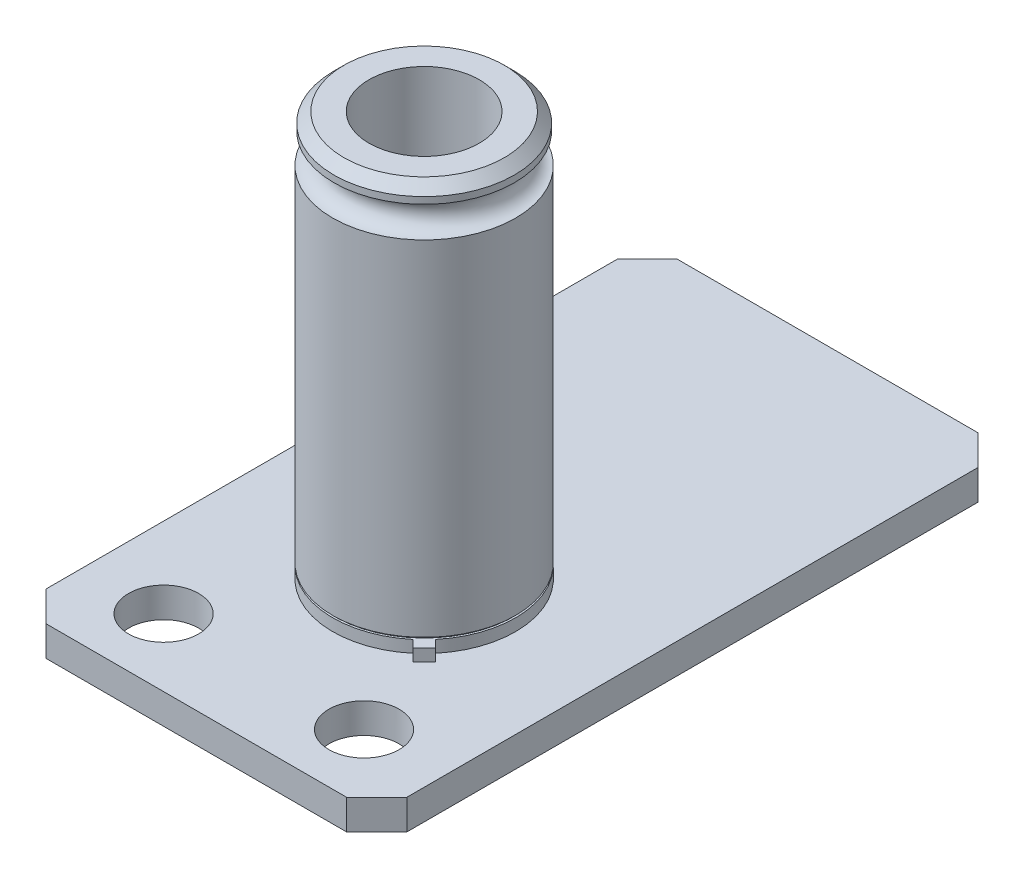
SolidWorks part; units mm, degrees
ref_plane "Piano frontale" through (0, 0, 0) normal (0, 0, 1) x (1, 0, 0)
ref_plane "Piano superiore" through (0, 0, 0) normal (0, 1, 0) x (1, 0, 0)
ref_plane "Piano destro" through (0, 0, 0) normal (1, 0, 0) x (0, 0, -1)
sketch "Schizzo1" plane through (0, 0, 0) normal (0, 1, 0) x (1, 0, 0)
  circle A0 centre (0, 0) radius 4.56
  dimension "D1" = 9.12
extrude "Estrusione-Estrusione1" add sketch "Schizzo1" along normal blind 19.5
sketch "Schizzo2" plane through (0, 0, 0) normal (0, 0, 1) x (1, 0, 0)
  line L0 (-4.56, 19.5) -> (-4.56, 0) construction
  line L1 (4.56, 19.5) -> (-4.56, 19.5) construction
  line L2 (0, 19.5) -> (0, 15.6496) construction
  circle A0 centre (-4.56, 17.92) radius 0.75
  dimension "D1" = 1.5
  dimension "D2" = 1.58
revolve "Taglia-Rivoluzione1" cut sketch "Schizzo2" angle 360 about L2
sketch "Schizzo3" plane through (0, 0, 0) normal (0, 0, 1) x (1, 0, 0)
  line L0 (0, 19.5) -> (0, 17.17) construction
  line L1 (-6.8929, 18.2289) -> (-4.5, 18.2289)
  line L2 (-6.8929, 18.2289) -> (-6.8929, 19.7375)
  line L3 (-6.8929, 19.7375) -> (-4.5, 19.7375)
  line L4 (-4.5, 18.2289) -> (-4.5, 19.7375)
  line L5 (-6.8929, 18.2289) -> (-4.5, 19.7375) construction
  line L6 (-6.8929, 19.7375) -> (-4.5, 18.2289) construction
  line L7 (4.56, 19.5) -> (-4.56, 19.5) construction
  line L8 (-4.56, 17.17) -> (4.56, 17.17) construction
  point P0 (-5.6964, 18.9832)
  dimension "D1" = 4.5
revolve "Taglia-Rivoluzione2" cut sketch "Schizzo3" angle 360 about L0
chamfer "Smusso1" distance 0.5 angle 45 1 edges at (0, 19.5, 4.5)
sketch "Schizzo4" plane through (0, 19.5, 0) normal (0, 1, 0) x (1, 0, 0)
  line L0 (0, 0) -> (4, 0)
  circle A0 centre (0, 0) radius 4 construction
hole_wizard "Foro per Vite M5-1" positions "Schizzo3D1" profile "Schizzo5" hole size "M5" standard "ISO" end condition up to next
sketch3d "Schizzo3D1"
  point P0 (0, 19.5, 0)
sketch "Schizzo5" plane through (0, 19.5, 0) normal (1, 0, 0) x (0, 0, 1)
  line L0 (0, 0) -> (0, 19.5)
  line L1 (0, 19.5) -> (2.75, 19.5)
  line L2 (2.75, 19.5) -> (2.75, 0)
  line L5 (2.75, 0) -> (0, 0)
  line L11 (0, -6.35) -> (0, 107.95) construction
  dimension "Thru Hole Dia." = 5.5
  dimension "Thru Hole Depth" = 19.5
cosmetic thread "Filettatura cosmetica1" parameters "D2"=16.5
sketch "Schizzo7" plane through (0, 0, 0) normal (0, 0, 1) x (1, 0, 0)
  line L0 (0, 0) -> (0, -0.7)
  line L1 (0, -0.7) -> (-4.56, -0.7)
  line L2 (-4.56, -0.7) -> (-4.56, -0.1)
  line L3 (-4.56, -0.1) -> (-4.46, -0.1)
  line L4 (-4.46, -0.1) -> (-4.46, 0)
  line L5 (-4.56, 0) -> (4.56, 0) construction
  line L6 (-4.46, 0) -> (0, 0)
  line L7 (0, 19.5) -> (4, 19.5) construction
  line L8 (-4.56, 17.17) -> (-4.56, 0) construction
  dimension "D1" = 20.2
  dimension "D2" = 0.1
  dimension "D3" = 0.1
revolve "Rivoluzione1" add sketch "Schizzo7" angle 360 about L0
sketch "Schizzo8" plane through (0, -0.7, 0) normal (0, -1, 0) x (1, 0, 0)
  line L0 (0, 0) -> (3.578, 3.578) construction
  line L1 (0, 0) -> (4, 0) construction
  line L2 (0.2828, -0.2828) -> (3.8608, 3.2951)
  line L3 (-0.2828, 0.2828) -> (3.2951, 3.8608)
  line L4 (3.8608, 3.2951) -> (3.578, 3.578)
  line L5 (3.578, 3.578) -> (3.2951, 3.8608)
  line L6 (-0.2828, 0.2828) -> (0.2828, -0.2828)
  line L7 (3.2244, 3.2244) -> (4.0701, 2.3787) construction
  circle A0 centre (0, 0) radius 4.56 construction
  dimension "D1" = 45
  dimension "D4" = 0.5
  dimension "D2" = 0.4
  dimension "D3" = 0.4
extrude "Estrusione-Estrusione2" add sketch "Schizzo8" against normal up to surface (0.6 mm away) up to face at (-4.56, -0.1, 0)
sketch "Schizzo9" plane through (0, -0.7, 0) normal (0, -1, 0) x (1, 0, 0)
  circle A0 centre (0, 0) radius 2.54 construction
  circle A1 centre (0, 2.54) radius 0.8 construction
  circle A2 centre (2.54, 0) radius 0.8
  circle A3 centre (0, -2.54) radius 0.8
  circle A4 centre (-2.54, 0) radius 0.8
  dimension "D1" = 5.08
  dimension "D2" = 1.6
extrude "Taglio-Estrusione1" cut sketch "Schizzo9" against normal up to surface (0.6 mm away) up to face at (1.7859, -0.1, 1.7859)
sketch "Schizzo10" plane through (0, -0.1, 0) normal (0, -1, 0) x (1, 0, 0)
  circle A0 centre (0, 0) radius 2.54 construction
  circle A1 centre (0, 2.54) radius 0.225
  circle A2 centre (2.54, 0) radius 0.225
  circle A3 centre (0, -2.54) radius 0.225
  circle A4 centre (-2.54, 0) radius 0.225
  dimension "D1" = 0.45
extrude "Estrusione-Estrusione3" add sketch "Schizzo10" along normal blind 13
ref_plane "Düzlem1" through (0, 0, 0) normal (0.7071, 0, -0.7071) x (-0.5774, -0.5774, -0.5774)
sketch "Çizim1" plane through (0, -0.7, 0) normal (0, -1, 0) x (-1, 0, 0)
  line L0 (0, 20.1329) -> (0, -11.0395) construction
  line L2 (-9, 11.3671) -> (-9, -11.3671)
  line L3 (-9, -11.3671) -> (9, -11.3671)
  line L4 (9, 14.7227) -> (9, -11.3671)
  line L8 (9, 14.7227) -> (9, 20.1329)
  line L9 (9, 20.1329) -> (-9, 20.1329)
  line L10 (-9, 11.3671) -> (-9, 20.1329)
  point P0 (0, 0)
  dimension "D1" = 18
  dimension "D2" = 31.5
extrude "Yükseklik-Ekstrüzyon1" add sketch "Çizim1" along normal blind 1.5
sketch "Çizim2" plane through (-9, 0, 0) normal (-1, 0, 0) x (0, 0, 1)
  line L1 (-2.9333, -2.4376) -> (3.5096, -2.4376)
  line L2 (-2.9333, -2.4376) -> (-2.9333, -13.3327)
  line L3 (-2.9333, -13.3327) -> (3.5096, -13.3327)
  line L4 (3.5096, -2.4376) -> (3.5096, -13.3327)
extrude "Kes-Ekstrüzyon1" cut sketch "Çizim2" against normal blind 13.5
sketch "Çizim3" plane through (0, -0.7, 0) normal (0, 1, 0) x (1, 0, 0)
  circle A0 centre (-5, -8) radius 1.75
  circle A1 centre (5, -8) radius 1.75
  dimension "D1" = 10
  dimension "D2" = 5
  dimension "D3" = 3.5
  dimension "D4" = 8
extrude "Kes-Ekstrüzyon2" cut sketch "Çizim3" against normal blind 13.5
sketch "Çizim4" plane through (0, -0.7, 0) normal (0, 1, 0) x (1, 0, 0)
  line L0 (-9, -9.8671) -> (-7.5, -11.3671)
  line L1 (-9, -11.3671) -> (-9, 20.1329) construction
  line L2 (9, -11.3671) -> (-9, -11.3671) construction
  line L3 (-7.5, -11.3671) -> (-9, -11.3671)
  line L4 (-9, -11.3671) -> (-9, -9.8671)
  line L5 (0, 0) -> (0, -7.1227) construction
  line L6 (9, -11.3671) -> (9, -9.8671)
  line L7 (7.5, -11.3671) -> (9, -11.3671)
  line L8 (9, -9.8671) -> (7.5, -11.3671)
  line L9 (-9, 4.3829) -> (9, 4.3829) construction
  line L10 (9, 20.1329) -> (9, -11.3671) construction
  line L11 (9, 18.6329) -> (7.5, 20.1329)
  line L12 (7.5, 20.1329) -> (9, 20.1329)
  line L13 (9, 20.1329) -> (9, 18.6329)
  line L14 (-9, 20.1329) -> (-9, 18.6329)
  line L15 (-7.5, 20.1329) -> (-9, 20.1329)
  line L16 (-9, 18.6329) -> (-7.5, 20.1329)
  dimension "D1" = 1.5
  dimension "D2" = 1.5
extrude "Kes-Ekstrüzyon3" cut sketch "Çizim4" against normal blind 13.5
